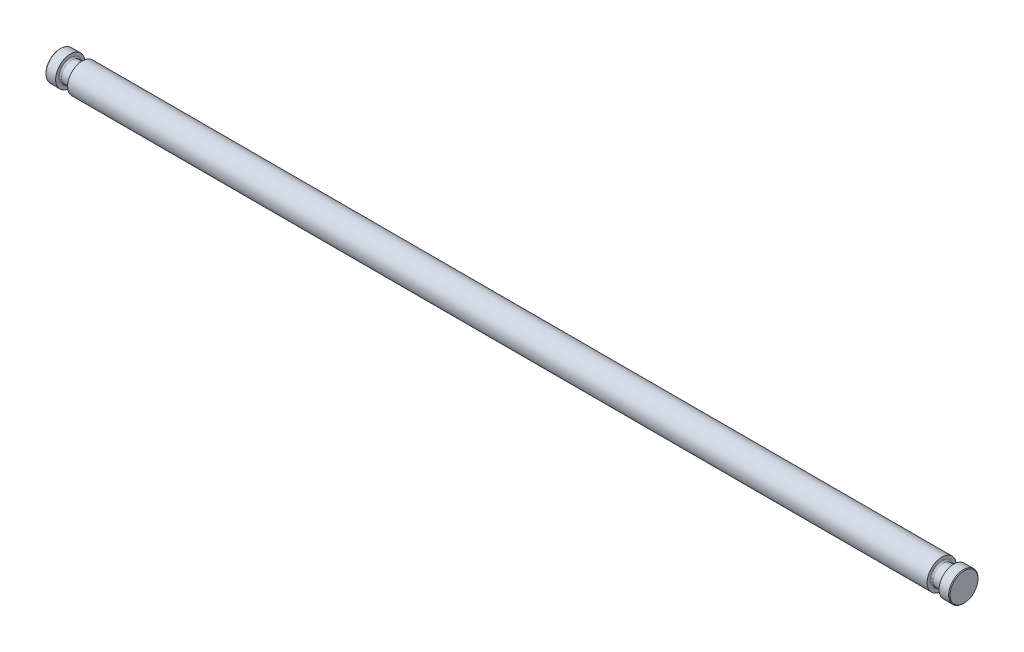
SolidWorks part; units mm, degrees
ref_plane "Front Plane" through (0, 0, 0) normal (0, 0, 1) x (1, 0, 0)
ref_plane "Top Plane" through (0, 0, 0) normal (0, 1, 0) x (1, 0, 0)
ref_plane "Right Plane" through (0, 0, 0) normal (1, 0, 0) x (0, 0, -1)
sketch "Sketch1" plane through (0, 0, 0) normal (0, 1, 0) x (1, 0, 0)
  line L0 (-976.376, 0) -> (-976.376, 31.7309)
  line L1 (-976.376, 31.7309) -> (-954.024, 31.7309)
  line L2 (-954.024, 31.7309) -> (-954.024, 22.0218)
  line L3 (-954.024, 22.0218) -> (-928.2176, 22.0218)
  line L4 (-928.2176, 22.0218) -> (-928.2176, 31.7309)
  line L5 (-928.2176, 31.7309) -> (928.3446, 31.7309)
  line L6 (928.3446, 31.7309) -> (928.3446, 22.0218)
  line L7 (928.3446, 22.0218) -> (954.151, 22.0218)
  line L8 (954.151, 22.0218) -> (954.151, 31.7309)
  line L9 (954.151, 31.7309) -> (976.376, 31.7309)
  line L10 (976.376, 31.7309) -> (976.376, 0)
  line L11 (976.376, 0) -> (-976.376, 0)
  line L12 (-1001.776, 0) -> (1001.776, 0) construction
  point P14 (0, 0)
  dimension "D1" = 22.225
  dimension "D2" = 48.0314
  dimension "D3" = 1904.5936
  dimension "D4" = 1930.4
  dimension "D5" = 1952.752
  dimension "D6" = 9.7092
  dimension "D7" = 31.7309
revolve "Revolve1" add sketch "Sketch1" angle 360 about L12
sketch "Sketch2" plane through (0, 0, 0) normal (0, 0, 1) x (1, 0, 0)
  line L1 (-941.1208, -6.35) -> (941.2478, -6.35)
  line L2 (-941.1208, -6.35) -> (-941.1208, 6.35)
  line L3 (-941.1208, 6.35) -> (941.2478, 6.35)
  line L4 (941.2478, -6.35) -> (941.2478, 6.35)
  point P8 (0, 0)
  dimension "D1" = 1882.3686
  dimension "D2" = 12.7
  dimension "D3" = 941.2478
  dimension "D4" = 6.35
extrude "Cut-Extrude2" cut sketch "Sketch2" against normal blind 63.4619 from offset 24.6062
fillet "Fillet1" radius 3.175 4 edges at (954.151, 0, 22.0218) (928.3446, 0, 22.0218) (-928.2176, 0, 22.0218) (-954.024, 0, 22.0218)
chamfer "Chamfer1" distance 1.524 angle 45 2 edges at (976.376, 0, 31.7309) (-976.376, 0, 31.7309)
